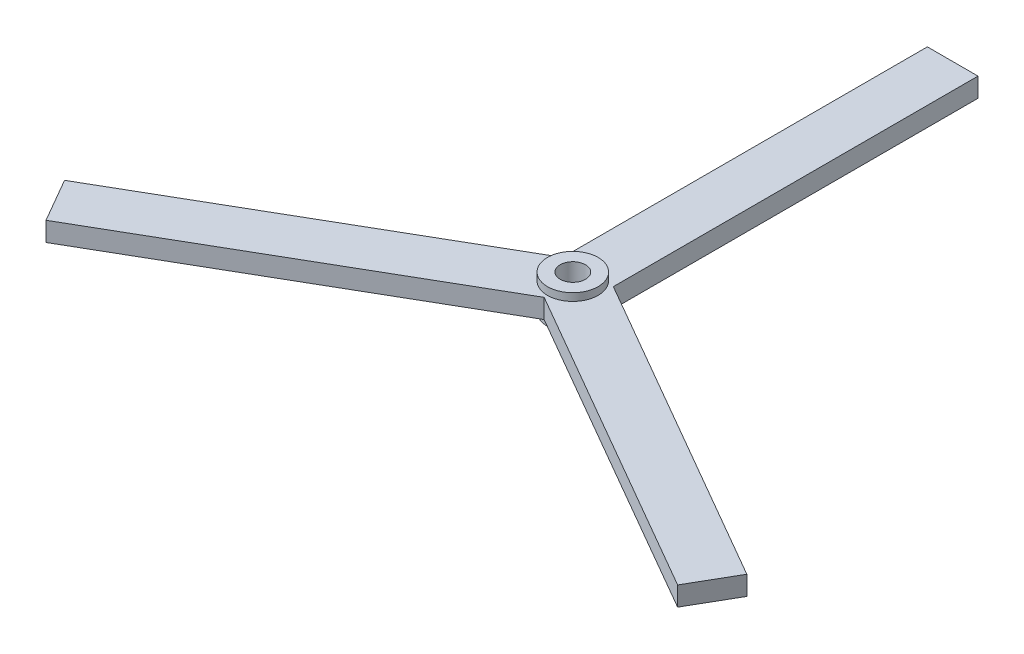
SolidWorks part; units mm, degrees
ref_plane "前视基准面" through (0, 0, 0) normal (0, 0, 1) x (1, 0, 0)
ref_plane "上视基准面" through (0, 0, 0) normal (0, 1, 0) x (1, 0, 0)
ref_plane "右视基准面" through (0, 0, 0) normal (1, 0, 0) x (0, 0, -1)
sketch "草图1" plane through (0, 0, 0) normal (0, 1, 0) x (1, 0, 0)
  circle A0 centre (0, 0) radius 65.9 construction
  circle A1 centre (0, 0) radius 2.5
  circle A2 centre (0, 0) radius 5
  dimension "D1" = 131.8
  dimension "D2" = 5
  dimension "D3" = 10
extrude "凸台-拉伸1" add sketch "草图1" along normal mid plane 6.8
sketch "草图2" plane through (0, 0, 0) normal (0, 1, 0) x (1, 0, 0)
  line L0 (0, 0) -> (0, 75) construction
  line L1 (5, 3.0025) -> (5, 75)
  line L2 (-5, 3.0025) -> (-5, 75)
  line L3 (-5, 75) -> (5, 75)
  line L4 (67.3517, -32.9963) -> (62.3517, -41.6565)
  line L5 (0, -5.6578) -> (62.3517, -41.6565)
  line L6 (5, 3.0025) -> (67.3517, -32.9963)
  line L7 (-62.3517, -41.6565) -> (-67.3517, -32.9963)
  line L8 (-5, 3.0025) -> (-67.3517, -32.9963)
  line L9 (0, -5.6578) -> (-62.3517, -41.6565)
  line L10 (5, 0) -> (5, 75) construction
  line L11 (-5, 0) -> (-5, 75) construction
  circle A0 centre (0, 0) radius 75 construction
  circle A1 centre (0, 0) radius 5 construction
  circle A3 centre (0, 0) radius 5
  dimension "D1" = 150
  dimension "D2" = 5
  dimension "D3" = 5
  dimension "D4" = 3
extrude "凸台-拉伸2" add sketch "草图2" along normal mid plane 3.8
